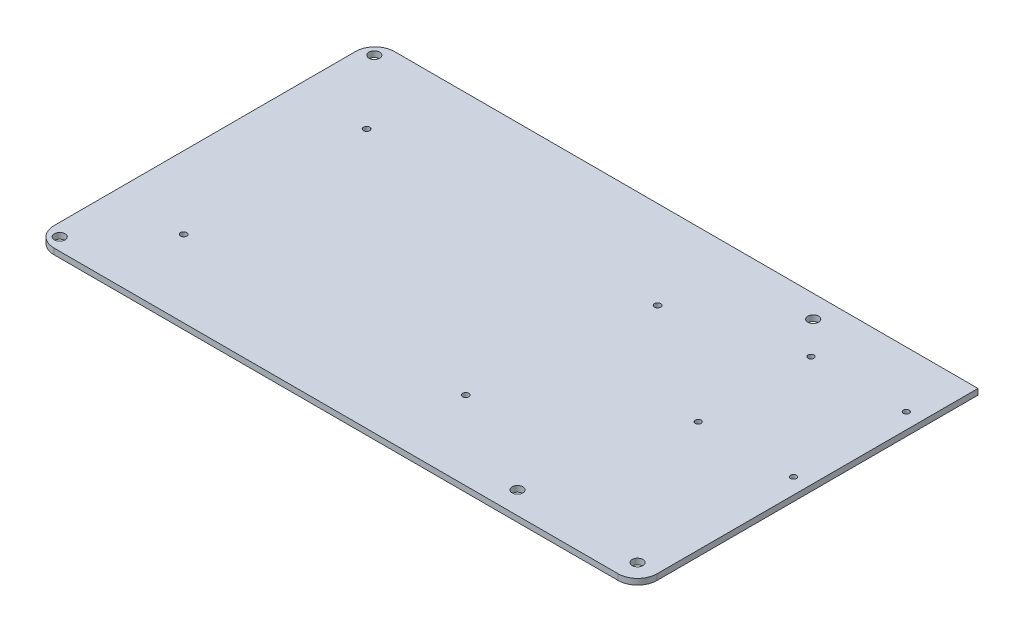
SolidWorks part; units mm, degrees
material "Custom Plastic"
ref_plane "Plan de face" through (0, 0, 0) normal (0, 0, 1) x (1, 0, 0)
ref_plane "Plan de dessus" through (0, 0, 0) normal (0, 1, 0) x (1, 0, 0)
ref_plane "Plan de droite" through (0, 0, 0) normal (1, 0, 0) x (0, 0, -1)
sketch "Esquisse1" plane through (0, 0, 0) normal (0, 1, 0) x (1, 0, 0)
  line L0 (-145, 87.5) -> (155, 87.5)
  line L1 (-155, 87.5) -> (155, 87.5) construction
  line L2 (-155, 87.5) -> (-155, -87.5) construction
  line L3 (-155, -87.5) -> (155, -87.5) construction
  line L4 (155, 87.5) -> (155, -87.5) construction
  line L5 (-155, 87.5) -> (155, -87.5) construction
  line L6 (-155, -87.5) -> (155, 87.5) construction
  line L7 (155, 87.5) -> (155, -77.5)
  line L8 (145, -87.5) -> (-145, -87.5)
  line L9 (-155, 77.5) -> (-155, -77.5)
  line L11 (-145, 87.5) -> (-145, 77.5) construction
  line L12 (145, -87.5) -> (145, -77.5) construction
  line L13 (145, -77.5) -> (155, -77.5) construction
  line L14 (-148.5355, 75.6928) -> (-148.5355, 80.6928) construction
  line L15 (-148.5355, -76.0355) -> (-148.5355, -81.0355) construction
  line L16 (-155, -77.5) -> (-145, -77.5) construction
  line L17 (-145, -77.5) -> (-145, -87.5) construction
  line L18 (-145, 77.5) -> (-155, 77.5) construction
  line L20 (-148.5355, -81.0355) -> (-152.0711, -84.5711) construction
  line L22 (146.9209, 58.7288) -> (155, 58.7288) construction
  line L24 (146.9209, 58.7288) -> (146.9209, 87.5) construction
  line L26 (155, 58.7288) -> (97.9209, 58.7288) construction
  line L27 (146.9209, 58.7288) -> (146.9209, 0.7288) construction
  line L28 (146.9209, 0.7288) -> (155, 0.7288) construction
  line L30 (146.9209, 0.7288) -> (97.9209, 0.7288) construction
  arc A0 (-155, 77.5) -> (-145, 87.5) centre (-145, 77.5) cw
  arc A1 (-155, -77.5) -> (-145, -87.5) centre (-145, -77.5) ccw
  arc A3 (155, -77.5) -> (145, -87.5) centre (145, -77.5) cw
  circle A14 centre (81.7862, 76) radius 2.75
  circle A18 centre (97.9209, 58.7288) radius 1.5
  circle A19 centre (-148.5355, 80.6928) radius 2.75
  circle A20 centre (-148.5355, -81.0355) radius 2.75
  circle A21 centre (146.9209, 58.7288) radius 1.5
  circle A22 centre (97.9209, 0.7288) radius 1.5
  circle A27 centre (146.9209, 0.7288) radius 1.5
  circle A29 centre (81.7862, -76) radius 2.75
  circle A32 centre (145, -77.5) radius 2.75
  circle A36 centre (81.7862, 76) radius 2.5 construction
  circle A37 centre (81.7862, -76) radius 2.5 construction
  point P4 (0, 0)
  point P18 (0, 0)
  dimension "D3" = 10
  dimension "D4" = 5.5
  dimension "D5" = 3
  dimension "D11" = 5
  dimension "D13" = 5.5
  dimension "D2" = 175
  dimension "D6" = 8.0791
  dimension "D7" = 28.7712
  dimension "D8" = 57.0791
  dimension "D9" = 58
  dimension "D10" = 49
  dimension "D12" = 5
  dimension "D20" = 310
extrude "Boss.-Extru.1" add sketch "Esquisse1" along normal blind 3
sketch "Sketch1" plane through (0, 3, 0) normal (0, 1, 0) x (1, 0, 0)
  line L0 (-155, 0) -> (155, 0) construction
  line L2 (155, -77.5) -> (155, 87.5) construction
  line L3 (-155, 0) -> (-117.6973, 45.8964) construction
  line L4 (-117.6973, 45.8964) -> (35.6685, 42.142) construction
  line L5 (35.6685, 42.142) -> (26.2757, -47.1235) construction
  line L6 (26.2757, -47.1235) -> (-117.7873, -48.0536) construction
  line L7 (-117.7873, -48.0536) -> (-155, 0) construction
  line L8 (-145, 87.5) -> (-155, 87.5) construction
  circle A1 centre (35.6685, 42.142) radius 1.6
  circle A2 centre (26.2757, -47.1235) radius 1.6
  circle A3 centre (-117.7873, -48.0536) radius 1.6
  circle A4 centre (-117.6973, 45.8964) radius 1.6
  dimension "D1" = 3.2
  dimension "D2" = 3.2
  dimension "D3" = 3.2
  dimension "D4" = 3.2
  dimension "D5" = 60.7777
  dimension "D6" = 59.1436
  dimension "D7" = 153.3659
  dimension "D8" = 89.7583
  dimension "D9" = 144.063
extrude "Cut-Extrude9" cut sketch "Sketch1" against normal blind 10
